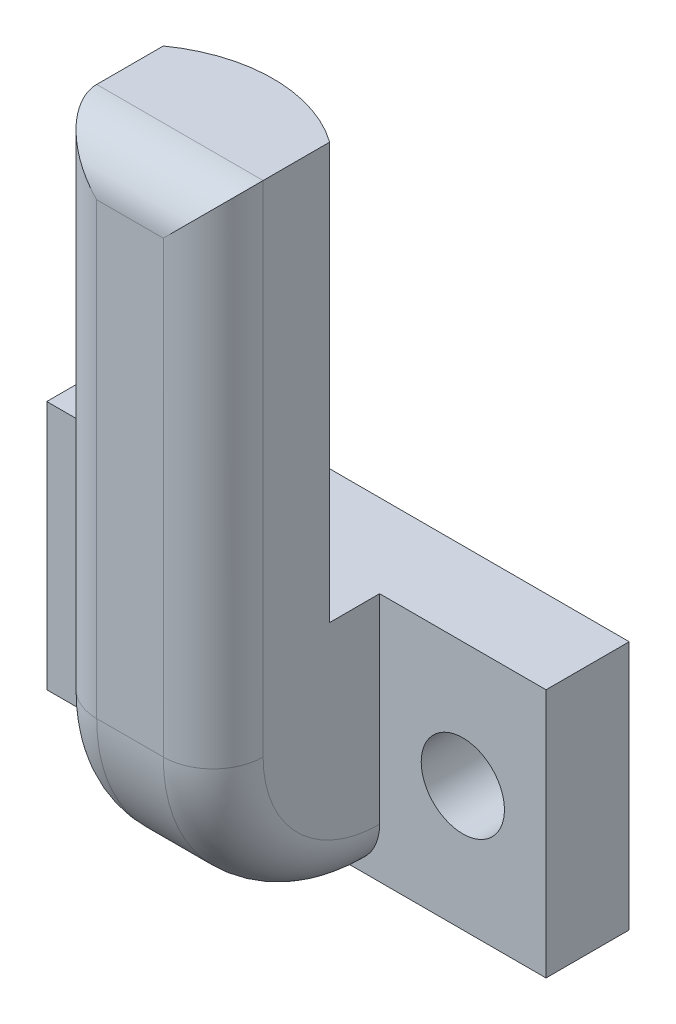
SolidWorks part; units mm, degrees
material "ABS"
ref_plane "Plan de face" through (0, 0, 0) normal (0, 0, 1) x (1, 0, 0)
ref_plane "Plan de dessus" through (0, 0, 0) normal (0, 1, 0) x (1, 0, 0)
ref_plane "Plan de droite" through (0, 0, 0) normal (1, 0, 0) x (0, 0, -1)
sketch "Esquisse1" plane through (0, 0, 0) normal (0, 0, 1) x (1, 0, 0)
  line L0 (0, -1000) -> (0, 49000) construction
  line L1 (-15, 7.5) -> (15, 7.5)
  line L2 (-15, 7.5) -> (-15, -7.5)
  line L3 (-15, -7.5) -> (15, -7.5)
  line L4 (15, 7.5) -> (15, -7.5)
  line L5 (-15, 7.5) -> (15, -7.5) construction
  line L6 (-15, -7.5) -> (15, 7.5) construction
  circle A0 centre (-10, 0) radius 2.5
  circle A1 centre (10, 0) radius 2.5
  point P0 (0, 0)
  dimension "D3" = 5
  dimension "D1" = 30
  dimension "D2" = 15
  dimension "D4" = 10
extrude "Boss.-Extru.2" add sketch "Esquisse1" along normal blind 5
sketch "Esquisse2" plane through (0, 0, 5) normal (0, 0, 1) x (1, 0, 0)
  line L0 (15, 7.5) -> (-15, 7.5) construction
  line L1 (5, -7.5) -> (-5, -7.5)
  line L2 (5, -7.5) -> (5, 7.5)
  line L3 (5, 7.5) -> (-5, 7.5)
  line L4 (-5, -7.5) -> (-5, 7.5)
  line L5 (5, -7.5) -> (-5, 7.5) construction
  line L6 (5, 7.5) -> (-5, -7.5) construction
  point P0 (0, 0)
  dimension "D1" = 10
extrude "Boss.-Extru.3" add sketch "Esquisse2" along normal blind 10
sketch "Esquisse3" plane through (0, 7.5, 0) normal (0, 1, 0) x (1, 0, 0)
  line L0 (5, -15) -> (-5, -15) construction
  line L1 (-5, -15) -> (-5, -5) construction
  line L2 (5, -15) -> (5, -5) construction
  line L3 (-5, -8) -> (-5, -15)
  line L4 (-5, -15) -> (5, -15)
  line L5 (5, -15) -> (5, -8)
  arc A0 (-5, -8) -> (5, -8) centre (0, -15) cw
  dimension "D1" = 7
extrude "Boss.-Extru.5" add sketch "Esquisse3" along normal blind 25
fillet "Congé1" radius 10 1 edges at (0, -7.5, 15)
fillet "Congé2" radius 3 5 edges at (-5, -4.5711, 12.0711) (-5, 17.5, 15) (0, 32.5, 15) (5, 17.5, 15) (5, -4.5711, 12.0711)
